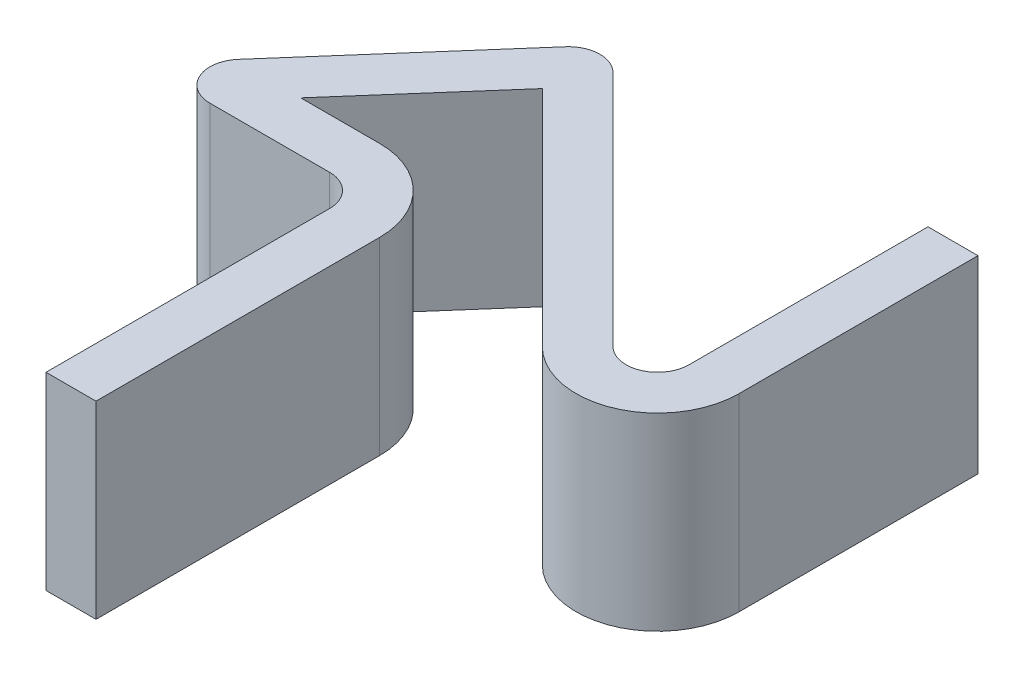
SolidWorks part; units mm, degrees
material "1060 Alloy"
ref_plane "Front Plane" through (0, 0, 0) normal (0, 0, 1) x (1, 0, 0)
ref_plane "Top Plane" through (0, 0, 0) normal (0, 1, 0) x (1, 0, 0)
ref_plane "Right Plane" through (0, 0, 0) normal (1, 0, 0) x (0, 0, -1)
sketch "Sketch8" plane through (0, 0, 0) normal (0, 1, 0) x (1, 0, 0)
  line L0 (0, 0) -> (0, 5) construction
  line L1 (0, 5) -> (-3.5, 5) construction
  line L2 (-3.5, 5) -> (0, 9) construction
  line L3 (0, 9) -> (5, 4) construction
  line L4 (5, 4) -> (5, 9) construction
  line L5 (0, 0) -> (0, 4.5)
  line L6 (-0.5, 5) -> (-2.3981, 5)
  line L7 (-2.7744, 5.8293) -> (-0.3519, 8.5978)
  line L8 (0.3779, 8.6221) -> (4.1464, 4.8536)
  line L9 (5, 5.2071) -> (5, 9)
  line L10 (0.7937, 0) -> (0.7937, 4.5)
  line L11 (-0.5, 5.7938) -> (-1.7508, 5.7938)
  line L12 (-1.7508, 5.7938) -> (0.0387, 7.8388)
  line L13 (0.0387, 7.8388) -> (3.5852, 4.2923)
  line L14 (5.7938, 5.2071) -> (5.7938, 9)
  line L15 (0, 0) -> (0.7937, 0)
  line L16 (5, 9) -> (5.7938, 9)
  arc A0 (0, 4.5) -> (-0.5, 5) centre (-0.5, 4.5) ccw
  arc A1 (-2.7744, 5.8293) -> (-2.3981, 5) centre (-2.3981, 5.5) ccw
  arc A2 (-0.3519, 8.5978) -> (0.3779, 8.6221) centre (0.0244, 8.2685) cw
  arc A3 (4.1464, 4.8536) -> (5, 5.2071) centre (4.5, 5.2071) ccw
  arc A4 (0.7937, 4.5) -> (-0.5, 5.7938) centre (-0.5, 4.5) ccw
  arc A5 (-1.7508, 5.7938) -> (-1.7508, 5.7938) centre (-1.7508, 5.7938) ccw
  arc A6 (0.0387, 7.8388) -> (0.0387, 7.8388) centre (0.0387, 7.8388) cw
  arc A7 (3.5852, 4.2923) -> (5.7938, 5.2071) centre (4.5, 5.2071) ccw
  point P33 (4.5, 3.9134)
  point P34 (-2.8981, 5.5)
  dimension "D6" = 0.5
  dimension "D1" = 3.5
  dimension "D2" = 4
  dimension "D3" = 5
  dimension "D4" = 5
  dimension "D5" = 5
  dimension "D8" = 8.6919
  dimension "D9" = 9
  dimension "D10" = 3.9134
  dimension "D11" = 5
  dimension "D7" = 0.7937
extrude "Boss-Extrude2" add sketch "Sketch8" along normal mid plane 3
